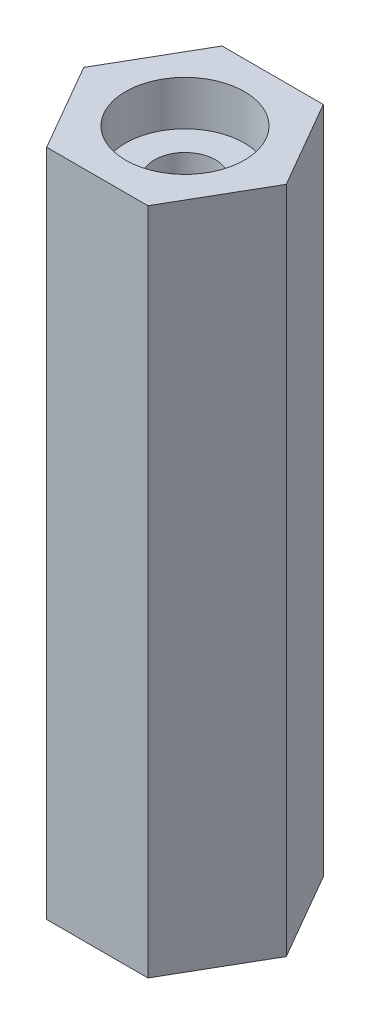
SolidWorks part; units mm, degrees
ref_plane "Alzado" through (0, 0, 0) normal (0, 0, 1) x (1, 0, 0)
ref_plane "Planta" through (0, 0, 0) normal (0, 1, 0) x (1, 0, 0)
ref_plane "Vista lateral" through (0, 0, 0) normal (1, 0, 0) x (0, 0, -1)
sketch "Croquis1" plane through (0, 0, 0) normal (0, 1, 0) x (1, 0, 0)
  line L1 (6.8127, 0) -> (3.4064, 5.9)
  line L2 (3.4064, 5.9) -> (-3.4064, 5.9)
  line L3 (-3.4064, 5.9) -> (-6.8127, 0)
  line L4 (-6.8127, 0) -> (-3.4064, -5.9)
  line L5 (-3.4064, -5.9) -> (3.4064, -5.9)
  line L6 (3.4064, -5.9) -> (6.8127, 0)
  circle A0 centre (0, 0) radius 5.9 construction
  dimension "D1" = 11.8
extrude "Saliente-Extruir1" add sketch "Croquis1" along normal blind 45
sketch "Croquis2" plane through (0, 45, 0) normal (0, 1, 0) x (1, 0, 0)
  circle A0 centre (0, 0) radius 4
  dimension "D1" = 8
extrude "Cortar-Extruir1" cut sketch "Croquis2" against normal blind 3
sketch "Croquis3" plane through (0, 42, 0) normal (0, 1, 0) x (1, 0, 0)
  circle A0 centre (0, 0) radius 2.05
  dimension "D1" = 4.1
extrude "Cortar-Extruir2" cut sketch "Croquis3" against normal blind 11
ref_plane "Plano1" through (0, 39.5, 0) normal (0, 1, 0) x (1, 0, 0)
sketch "Croquis4" plane through (0, 39.5, 0) normal (0, 1, 0) x (1, 0, 0)
  line L0 (-1.4491, 1.45) -> (1.4491, 1.45)
  arc A1 (1.4491, 1.45) -> (-1.4491, 1.45) centre (0, 0) ccw
  dimension "D1" = 1.45
extrude "Saliente-Extruir2" add sketch "Croquis4" against normal blind 11
